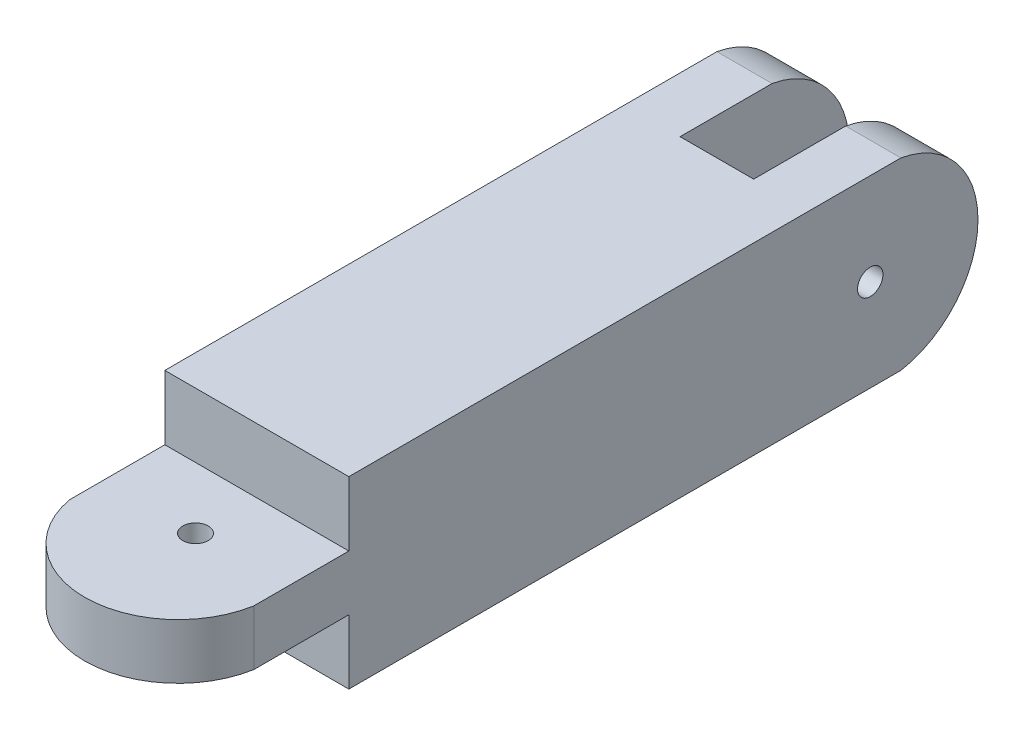
SolidWorks part; units mm, degrees
ref_plane "Front Plane" through (0, 0, 0) normal (0, 0, 1) x (1, 0, 0)
ref_plane "Top Plane" through (0, 0, 0) normal (0, 1, 0) x (1, 0, 0)
ref_plane "Right Plane" through (0, 0, 0) normal (1, 0, 0) x (0, 0, -1)
sketch "Sketch2" plane through (0, 0, 0) normal (0, 0, 1) x (1, 0, 0)
  line L1 (-30, 30) -> (30, 30)
  line L2 (-30, 30) -> (-30, -30)
  line L3 (-30, -30) -> (30, -30)
  line L4 (30, 30) -> (30, -30)
  line L5 (-30, 30) -> (30, -30) construction
  line L6 (-30, -30) -> (30, 30) construction
  point P0 (0, 0)
  dimension "D1" = 60
  dimension "D2" = 60
extrude "Boss-Extrude1" add sketch "Sketch2" along normal blind 150
ref_plane "Plane1" through (0, 0, 0) normal (0, 0, -1) x (-1, 0, 0)
sketch "Sketch3" plane through (0, 0, 0) normal (0, 0, -1) x (-1, 0, 0)
  line L0 (-30, 30) -> (30, 30) construction
  line L1 (30, -30) -> (12, -30)
  line L2 (30, -30) -> (30, 30)
  line L3 (30, 30) -> (12, 30)
  line L4 (12, -30) -> (12, 30)
  line L5 (30, -30) -> (-30, -30) construction
  line L6 (-30, 30) -> (-12, 30)
  line L7 (-30, 30) -> (-30, -30)
  line L8 (-30, -30) -> (-12, -30)
  line L9 (-12, 30) -> (-12, -30)
  dimension "D1" = 18
  dimension "D2" = 18
extrude "Boss-Extrude2" add sketch "Sketch3" along normal blind 30
ref_plane "Plane2" through (30, 0, 0) normal (1, 0, 0) x (0, 0, -1)
sketch "Sketch4" plane through (30, 0, 0) normal (1, 0, 0) x (0, 0, -1)
  line L0 (30, 30) -> (30, -30)
  arc A0 (30, 30) -> (30, -30) centre (24.6689, 0) cw
  dimension "D1" = 30.47
extrude "Boss-Extrude3" add sketch "Sketch4" against normal blind 18
ref_plane "Plane3" through (-30, 0, 0) normal (-1, 0, 0) x (0, 0, 1)
sketch "Sketch5" plane through (-30, 0, 0) normal (-1, 0, 0) x (0, 0, 1)
  line L0 (-30, -30) -> (-30, 30)
  arc A0 (-30, -30) -> (-30, 30) centre (-24.6689, 0) cw
  dimension "D1" = 30.47
extrude "Boss-Extrude4" add sketch "Sketch5" against normal blind 18
ref_plane "Plane4" through (0, 0, 150) normal (0, 0, 1) x (1, 0, 0)
sketch "Sketch6" plane through (0, 0, 150) normal (0, 0, 1) x (1, 0, 0)
  line L0 (30, -30) -> (30, 30) construction
  line L1 (-30, 9) -> (30, 9)
  line L2 (-30, 9) -> (-30, -9)
  line L3 (-30, -9) -> (30, -9)
  line L4 (30, 9) -> (30, -9)
  line L5 (-30, 9) -> (30, -9) construction
  line L6 (-30, -9) -> (30, 9) construction
  point P0 (0, 0)
  dimension "D1" = 18
extrude "Boss-Extrude5" add sketch "Sketch6" along normal blind 31
ref_plane "Plane5" through (0, 9, 0) normal (0, 1, 0) x (1, 0, 0)
sketch "Sketch7" plane through (0, 9, 0) normal (0, 1, 0) x (1, 0, 0)
  line L0 (30, -181) -> (-30, -181)
  arc A0 (30, -181) -> (-30, -181) centre (0, -175.6689) cw
  dimension "D1" = 30.47
extrude "Boss-Extrude6" add sketch "Sketch7" against normal blind 18
ref_plane "Plane6" through (0, 0, 150) normal (0, 0, 1) x (1, 0, 0)
sketch "Sketch8" plane through (0, 0, 150) normal (0, 0, 1) x (1, 0, 0)
  line L1 (-25.25, -25.25) -> (25.25, -25.25)
  line L2 (-25.25, -25.25) -> (-25.25, 25.25)
  line L3 (-25.25, 25.25) -> (25.25, 25.25)
  line L4 (25.25, -25.25) -> (25.25, 25.25)
  line L5 (-25.25, -25.25) -> (25.25, 25.25) construction
  line L6 (-25.25, 25.25) -> (25.25, -25.25) construction
  point P0 (0, 0)
  dimension "D1" = 50.5
  dimension "D2" = 50.5
extrude "Cut-Extrude2" cut sketch "Sketch8" against normal blind 130 and the other way blind 5 from offset 10 contours L3 L4 L1 L2 offset against normal yes
ref_plane "Plane7" through (0, -9, 0) normal (0, -1, 0) x (-1, 0, 0)
sketch "Sketch9" plane through (0, -9, 0) normal (0, -1, 0) x (-1, 0, 0)
  line L0 (30, -150) -> (-30, -150) construction
  circle A0 centre (0, -170) radius 4.15
  dimension "D1" = 8.3
  dimension "D2" = 20
extrude "Cut-Extrude3" cut sketch "Sketch9" against normal blind 130
ref_plane "Plane8" through (30, 0, 0) normal (1, 0, 0) x (0, 0, -1)
ref_plane "Plane9" through (12, 0, 0) normal (-1, 0, 0) x (0, 0, 1)
sketch "Sketch11" plane through (12, 0, 0) normal (-1, 0, 0) x (0, 0, 1)
  line L0 (0, -30) -> (0, 30) construction
  circle A0 centre (-20, 0) radius 4.15
  dimension "D2" = 8.3
  dimension "D1" = 20
extrude "Cut-Extrude4" cut sketch "Sketch11" against normal through all
ref_plane "Plane10" through (-12, 0, 0) normal (1, 0, 0) x (0, 0, -1)
sketch "Sketch12" plane through (-12, 0, 0) normal (1, 0, 0) x (0, 0, -1)
  line L0 (0, 30) -> (0, -30) construction
  circle A0 centre (20, 0) radius 4.15
  dimension "D1" = 20
  dimension "D2" = 8.3
extrude "Cut-Extrude5" cut sketch "Sketch12" against normal through all
